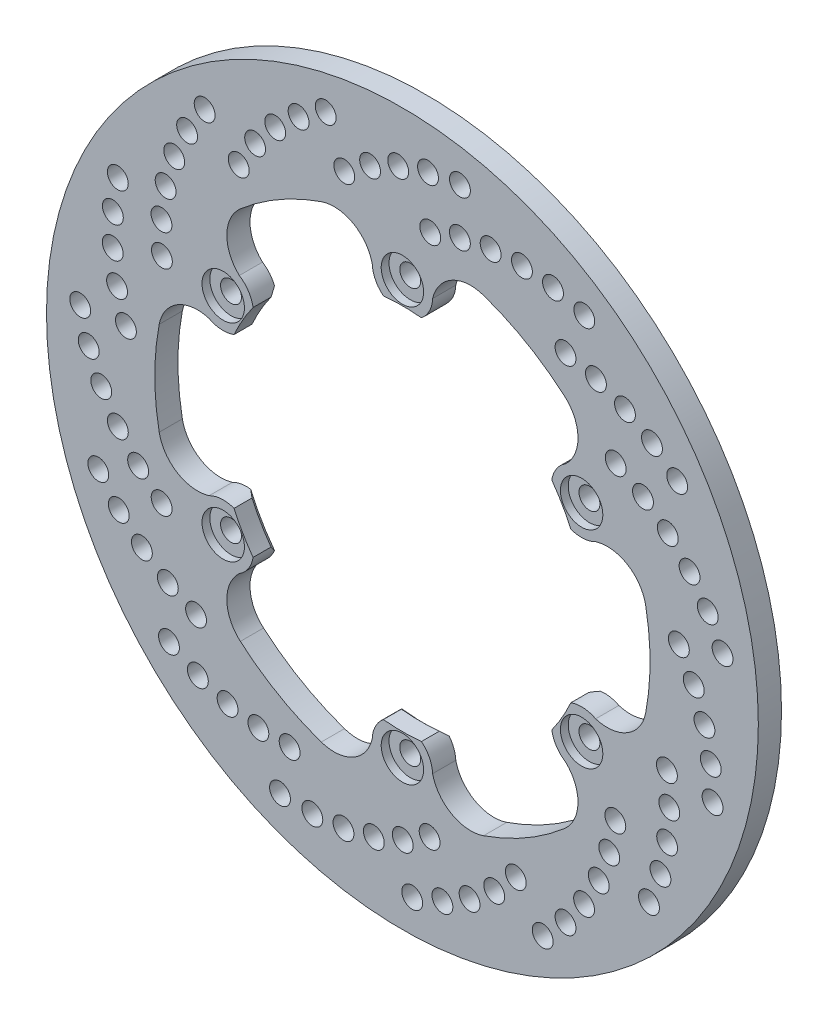
SolidWorks part; units mm, degrees
ref_plane "Front Plane" through (0, 0, 0) normal (0, 0, 1) x (1, 0, 0)
ref_plane "Top Plane" through (0, 0, 0) normal (0, 1, 0) x (1, 0, 0)
ref_plane "Right Plane" through (0, 0, 0) normal (1, 0, 0) x (0, 0, -1)
sketch "Sketch1" plane through (0, 0, 0) normal (0, 0, 1) x (1, 0, 0)
  circle A0 centre (0, 0) radius 136.525
  circle A1 centre (0, 0) radius 70.745
  dimension "D1" = 273.05
  dimension "D2" = 141.49
extrude "Boss-Extrude1" add sketch "Sketch1" along normal blind 8.89
hole_wizard "CBORE for 5/16 Pan Head Machine Screw1" positions "Sketch3" profile "Sketch2" counterbore size "5/16" standard "ANSI Inch" end condition through all
sketch "Sketch3" plane through (0, 0, 8.89) normal (0, 0, 1) x (1, 0, 0)
  point P0 (0, 79.375)
  dimension "D1" = 79.375
sketch "Sketch2" plane through (0, 79.375, 8.89) normal (1, 0, 0) x (0, -1, 0)
  line L0 (0, 0) -> (0, 8.89)
  line L1 (0, 8.89) -> (4.0132, 8.89)
  line L3 (4.0132, 8.89) -> (4.0132, 2.9972)
  line L4 (4.0132, 2.9972) -> (8.1356, 2.9972)
  line L5 (8.1356, 2.9972) -> (8.1356, 0)
  line L7 (8.1356, 0) -> (0, 0)
  line L11 (0, -6.35) -> (0, 107.95) construction
  dimension "Thru Hole Dia." = 8.0264
  dimension "Thru Hole Depth" = 8.89
  dimension "C'Bore Dia." = 16.2712
  dimension "C'Bore Depth" = 2.9972
pattern_circular "CirPattern1" count 6 over 360 about axis through (0, 0, 0) along (0, 0, 1) of "CBORE for 5/16 Pan Head Machine Screw1"
chamfer "Chamfer1" distance 2 angle 45 1 edges at (70.745, 0, 0)
sketch "Sketch4" plane through (0, 0, 8.89) normal (0, 0, 1) x (1, 0, 0)
  line L0 (0, 79.375) -> (0, 0) construction
  line L1 (0, 0) -> (-68.7408, 39.6875) construction
  line L2 (0, 0) -> (-58.1681, 100.7501) construction
  arc A0 (-31.1271, 89.7558) -> (-62.1672, 71.8348) centre (0, 0) ccw
  arc A1 (62.1672, 71.8348) -> (31.1271, 89.7558) centre (0, 0) ccw
  arc A2 (31.1271, 89.7558) -> (11.5872, 78.9165) centre (26.2123, 75.5838) ccw
  arc A3 (62.1672, 71.8348) -> (62.5501, 49.4931) centre (52.3514, 60.4924) cw
  arc A4 (-62.1672, 71.8348) -> (-62.5501, 49.4931) centre (-52.3514, 60.4924) ccw
  arc A5 (-31.1271, 89.7558) -> (-11.5872, 78.9165) centre (-26.2123, 75.5838) cw
  arc A6 (62.5501, 49.4931) -> (57.2883, 41.5079) centre (68.7408, 39.6875) ccw
  arc A7 (7.3028, 70.3671) -> (11.5872, 78.9165) centre (0, 79.375) ccw
  arc A8 (93.2944, -17.921) -> (93.2944, 17.921) centre (0, 0) ccw
  arc A9 (93.2944, 17.921) -> (74.1373, 29.4234) centre (78.5637, 15.0914) ccw
  arc A10 (93.2944, -17.921) -> (74.1373, -29.4234) centre (78.5637, -15.0914) cw
  arc A11 (74.1373, -29.4234) -> (64.5911, -28.8591) centre (68.7408, -39.6875) ccw
  arc A12 (64.5911, 28.8591) -> (74.1373, 29.4234) centre (68.7408, 39.6875) ccw
  arc A13 (31.1271, -89.7558) -> (62.1672, -71.8348) centre (0, 0) ccw
  arc A14 (62.1672, -71.8348) -> (62.5501, -49.4931) centre (52.3514, -60.4924) ccw
  arc A15 (31.1271, -89.7558) -> (11.5872, -78.9165) centre (26.2123, -75.5838) cw
  arc A16 (11.5872, -78.9165) -> (7.3028, -70.3671) centre (0, -79.375) ccw
  arc A17 (57.2883, -41.5079) -> (62.5501, -49.4931) centre (68.7408, -39.6875) ccw
  arc A18 (-62.1672, -71.8348) -> (-31.1271, -89.7558) centre (0, 0) ccw
  arc A19 (-31.1271, -89.7558) -> (-11.5872, -78.9165) centre (-26.2123, -75.5838) ccw
  arc A20 (-62.1672, -71.8348) -> (-62.5501, -49.4931) centre (-52.3514, -60.4924) cw
  arc A21 (-62.5501, -49.4931) -> (-57.2883, -41.5079) centre (-68.7408, -39.6875) ccw
  arc A22 (-7.3028, -70.3671) -> (-11.5872, -78.9165) centre (0, -79.375) ccw
  arc A23 (-93.2944, 17.921) -> (-93.2944, -17.921) centre (0, 0) ccw
  arc A24 (-93.2944, -17.921) -> (-74.1373, -29.4234) centre (-78.5637, -15.0914) ccw
  arc A25 (-93.2944, 17.921) -> (-74.1373, 29.4234) centre (-78.5637, 15.0914) cw
  arc A26 (-74.1373, 29.4234) -> (-64.5911, 28.8591) centre (-68.7408, 39.6875) ccw
  arc A27 (-64.5911, -28.8591) -> (-74.1373, -29.4234) centre (-68.7408, -39.6875) ccw
  arc A28 (-57.2883, 41.5079) -> (-64.5911, 28.8591) centre (0, 0) ccw
  arc A29 (7.3028, 70.3671) -> (-7.3028, 70.3671) centre (0, 0) ccw
  arc A30 (64.5911, 28.8591) -> (57.2883, 41.5079) centre (0, 0) ccw
  arc A31 (57.2883, -41.5079) -> (64.5911, -28.8591) centre (0, 0) ccw
  arc A32 (-7.3028, -70.3671) -> (7.3028, -70.3671) centre (0, 0) ccw
  arc A33 (-11.5872, 78.9165) -> (-7.3028, 70.3671) centre (0, 79.375) ccw
  arc A34 (-57.2883, 41.5079) -> (-62.5501, 49.4931) centre (-68.7408, 39.6875) ccw
  arc A35 (-64.5911, -28.8591) -> (-57.2883, -41.5079) centre (0, 0) ccw
  circle A36 centre (0, 0) radius 70.745 construction
  circle A37 centre (0, 0) radius 79.7627 construction
  point P67 (0, 0)
  dimension "D1" = 15
  dimension "D3" = 15
  dimension "D2" = 6
  dimension "D4" = 95
  dimension "D5" = 30
extrude "Cut-Extrude1" cut sketch "Sketch4" against normal through all
ref_plane "Mid Plane" through (0, 0, 4.445) normal (0, 0, 1) x (1, 0, 0)
sketch "Sketch5" plane through (0, 0, 8.89) normal (0, 0, 1) x (1, 0, 0)
  line L0 (0, 95) -> (0, 125) construction
  line L1 (0, 0) -> (68.7408, 39.6875) construction
  circle A0 centre (0, 0) radius 95 construction
  circle A1 centre (0, 0) radius 125 construction
  arc A2 (0, 95) -> (73.7567, 100.9205) centre (42.76, 24.6875) cw construction
  circle A3 centre (10.6802, 100.4711) radius 4
  circle A4 centre (22.0426, 104.3308) radius 4
  circle A5 centre (33.8454, 106.497) radius 4
  circle A6 centre (45.8378, 106.9237) radius 4
  circle A7 centre (57.7648, 105.6018) radius 4
  circle A8 centre (69.7648, 102.4243) radius 4
  circle A9 centre (62.572, 86.3454) radius 4
  circle A10 centre (74.2356, 83.5237) radius 4
  circle A11 centre (85.3647, 79.0357) radius 4
  circle A12 centre (95.7229, 72.977) radius 4
  circle A13 centre (105.393, 65.1933) radius 4
  circle A14 centre (92.2822, 53.4301) radius 4
  circle A15 centre (101.7897, 46.1084) radius 4
  circle A16 centre (110.1313, 37.4818) radius 4
  circle A17 centre (117.1296, 27.7338) radius 4
  circle A18 centre (122.7978, 16.6899) radius 4
  circle A19 centre (106.036, 11.2763) radius 4
  circle A20 centre (111.7435, 0.7205) radius 4
  circle A21 centre (115.8552, -10.5531) radius 4
  circle A22 centre (118.2836, -22.3048) radius 4
  circle A23 centre (118.9698, -34.6994) radius 4
  circle A24 centre (101.4552, -32.8273) radius 4
  circle A25 centre (102.3758, -44.792) radius 4
  circle A26 centre (101.5466, -56.7633) radius 4
  circle A27 centre (98.9852, -68.4867) radius 4
  circle A28 centre (94.5708, -80.0889) radius 4
  circle A29 centre (79.3318, -71.2548) radius 4
  circle A30 centre (75.3064, -82.5595) radius 4
  circle A31 centre (69.6797, -93.1586) radius 4
  circle A32 centre (62.5714, -102.8267) radius 4
  circle A33 centre (53.8196, -111.6302) radius 4
  circle A34 centre (43.4913, -97.3617) radius 4
  circle A35 centre (35.2159, -106.0517) radius 4
  circle A36 centre (25.7646, -113.4459) radius 4
  circle A37 centre (15.3385, -119.3869) radius 4
  circle A38 centre (3.7626, -123.8697) radius 4
  circle A39 centre (0.1307, -106.6338) radius 4
  circle A40 centre (-10.9638, -111.2067) radius 4
  circle A41 centre (-22.6055, -114.1174) radius 4
  circle A42 centre (-34.5467, -115.3041) radius 4
  circle A43 centre (-46.9451, -114.691) radius 4
  circle A44 centre (-43.2525, -97.468) radius 4
  circle A45 centre (-55.2478, -97.1329) radius 4
  circle A46 centre (-67.0669, -95.0569) radius 4
  circle A47 centre (-78.4583, -91.2842) radius 4
  circle A48 centre (-89.5355, -85.6811) radius 4
  circle A49 centre (-79.1569, -71.4491) radius 4
  circle A50 centre (-89.9789, -66.2641) radius 4
  circle A51 centre (-99.9318, -59.5603) radius 4
  circle A52 centre (-108.8039, -51.4803) radius 4
  circle A53 centre (-116.6444, -41.8563) radius 4
  circle A54 centre (-101.3744, -33.076) radius 4
  circle A55 centre (-109.1518, -23.9375) radius 4
  circle A56 centre (-115.5176, -13.7651) radius 4
  circle A57 centre (-120.3362, -2.7751) radius 4
  circle A58 centre (-123.5844, 9.2059) radius 4
  circle A59 centre (-106.0633, 11.0163) radius 4
  circle A60 centre (-109.4514, 22.528) radius 4
  circle A61 centre (-111.1293, 34.4102) radius 4
  circle A62 centre (-111.0614, 46.41) radius 4
  circle A63 centre (-109.1556, 58.6764) radius 4
  circle A64 centre (-92.4129, 53.2037) radius 4
  circle A65 centre (-90.8259, 65.0983) radius 4
  circle A66 centre (-87.5258, 76.6356) radius 4
  circle A67 centre (-82.583, 87.5703) radius 4
  circle A68 centre (-75.8528, 98.0011) radius 4
  circle A69 centre (-62.7835, 86.1917) radius 4
  circle A70 centre (-56.4957, 96.4125) radius 4
  circle A71 centre (-48.7883, 105.6101) radius 4
  circle A72 centre (-39.8252, 113.589) radius 4
  circle A73 centre (-29.4343, 120.3806) radius 4
  circle A74 centre (-22.2983, 104.2764) radius 4
  circle A75 centre (-12.3969, 111.056) radius 4
  circle A76 centre (-1.6148, 116.3236) radius 4
  circle A77 centre (9.8187, 119.9671) radius 4
  circle A78 centre (22.0736, 121.9451) radius 4
  circle A79 centre (50.6221, 87.4409) radius 4 [skipped]
  circle A80 centre (81.811, 59.2913) radius 4
  circle A81 centre (98.8541, 20.8898) radius 4 [skipped]
  circle A82 centre (98.8043, -21.1238) radius 4 [skipped]
  circle A83 centre (81.6704, -59.4849) radius 4
  circle A84 centre (50.4149, -87.5605) radius 4 [skipped]
  circle A85 centre (10.4423, -100.4961) radius 4
  circle A86 centre (-31.3359, -96.055) radius 4 [skipped]
  circle A87 centre (-67.6959, -75.0051) radius 4 [skipped]
  circle A88 centre (-92.3506, -40.9862) radius 4
  circle A89 centre (-101.0371, 0.1196) radius 4 [skipped]
  circle A90 centre (-92.2533, 41.2048) radius 4
  circle A91 centre (-67.5181, 75.1652) radius 4 [skipped]
  circle A92 centre (-31.1084, 96.1289) radius 4 [skipped]
  point P164 (0, 0)
  point P194 (0, 0)
  dimension "D1" = 250
  dimension "D2" = 190
  dimension "D5" = 8
  dimension "D7" = 12
  dimension "D8" = 12
  dimension "D12" = 8
  dimension "D13" = 8
  dimension "D14" = 8
  dimension "D15" = 8
  dimension "D16" = 8
  dimension "D3" = 79.375
  dimension "D4" = 30
  dimension "D6" = 12
  dimension "D9" = 12
  dimension "D10" = 12
  dimension "D11" = 12
  dimension "D17" = 15
  dimension "D18" = 15
extrude "Cut-Extrude4" cut sketch "Sketch5" against normal through all
